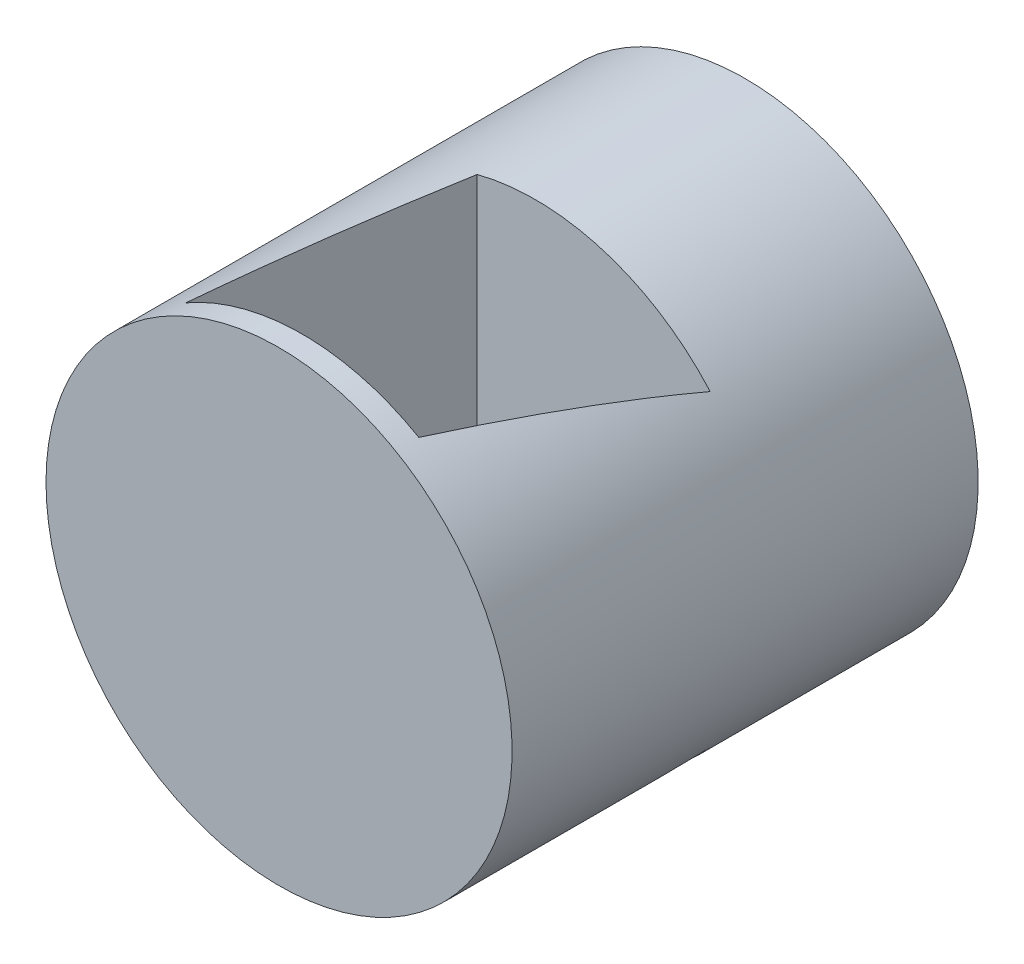
SolidWorks part; units mm, degrees
ref_plane "Front Plane" through (0, 0, 0) normal (0, 0, 1) x (1, 0, 0)
ref_plane "Top Plane" through (0, 0, 0) normal (0, 1, 0) x (1, 0, 0)
ref_plane "Right Plane" through (0, 0, 0) normal (1, 0, 0) x (0, 0, -1)
sketch "Sketch1" plane through (0, 0, 0) normal (0, 1, 0) x (1, 0, 0)
  line L0 (0, 10) -> (0, -10)
  line L1 (0, -10) -> (10, -10)
  line L2 (10, 10) -> (10, -10)
  line L3 (10, 10) -> (0, 10)
  dimension "D2" = 20
  dimension "D3" = 10
revolve "Revolve1" add sketch "Sketch1" angle 360 about L0
sketch "Sketch3" plane through (0, 0, 0) normal (0, 1, 0) x (1, 0, 0)
  line L0 (0, 3.8668) -> (0, -11.1606) construction
  line L1 (0, -10) -> (-5, -10) construction
  line L2 (-10, -10) -> (10, -10) construction
  line L3 (5, -9) -> (-5, -9)
  line L5 (-2.5, 1) -> (-5, -9)
  line L6 (-2.5, 1) -> (7.5, 1)
  line L7 (5, -9) -> (7.5, 1)
  dimension "D2" = 10
  dimension "D1" = 10
extrude "Cut-Extrude1" cut sketch "Sketch3" along normal mid plane 26 contours L6 L7 L3 L5
hole_wizard "Ø2.0mm Dowel Hole1" positions "Sketch5" profile "Sketch6" hole size "Ø2.0" standard "ANSI Metric"
sketch "Sketch5" plane through (0, 0, -10) normal (0, 0, -1) x (-1, 0, 0)
  point P0 (0, 0)
sketch "Sketch6" plane through (0, 0, -10) normal (1, 0, 0) x (0, 1, 0)
  line L0 (0, 0) -> (0, 10.6009)
  line L1 (0, 10.6009) -> (1, 10)
  line L2 (1, 10) -> (1, 0)
  line L5 (1, 0) -> (0, 0)
  line L10 (0, 10.6009) -> (-1, 10) construction
  line L11 (0, -6.35) -> (0, 107.95) construction
  dimension "Hole Dia." = 2
  dimension "Hole Depth" = 10
  dimension "Drill Angle" = 118
